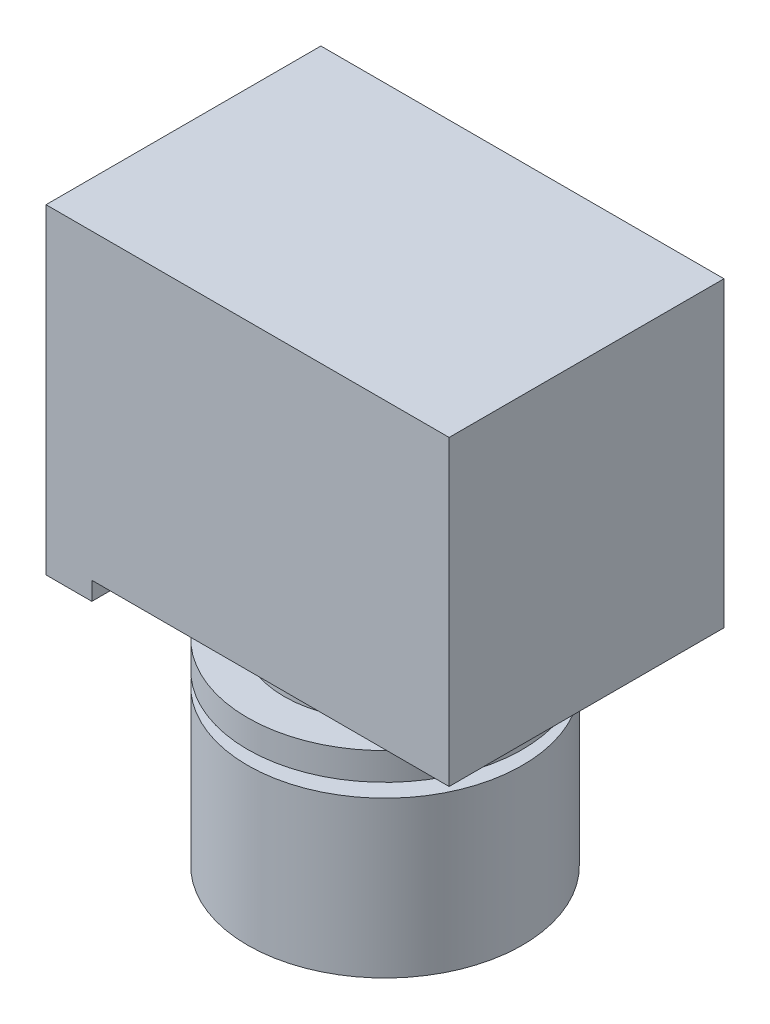
SolidWorks part; units mm, degrees
ref_plane "前基準面" through (0, 0, 0) normal (0, 0, 1) x (1, 0, 0)
ref_plane "上基準面" through (0, 0, 0) normal (0, 1, 0) x (1, 0, 0)
ref_plane "右基準面" through (0, 0, 0) normal (1, 0, 0) x (0, 0, -1)
sketch "草圖1" plane through (0, 0, 0) normal (0, 1, 0) x (1, 0, 0)
  circle A0 centre (0, 0) radius 15
  dimension "D1" = 30
extrude "伸長1" add sketch "草圖1" along normal blind 17
sketch "草圖2" plane through (0, 17, 0) normal (0, 1, 0) x (1, 0, 0)
  circle A0 centre (0, 0) radius 11
  dimension "D1" = 22
extrude "伸長2" add sketch "草圖2" along normal blind 1.5
sketch "草圖3" plane through (0, 18.5, 0) normal (0, 1, 0) x (1, 0, 0)
  circle A0 centre (0, 0) radius 15
  dimension "D1" = 30
extrude "伸長3" add sketch "草圖3" along normal blind 3
sketch "草圖4" plane through (0, 21.5, 0) normal (0, 1, 0) x (1, 0, 0)
  circle A0 centre (0, 0) radius 11
  dimension "D1" = 22
extrude "伸長4" add sketch "草圖4" along normal blind 4.5
cosmetic thread "裝飾螺紋線1" parameters "D2"=20.5
sketch "草圖6" plane through (0, 26, 0) normal (0, 1, 0) x (1, 0, 0)
  line L0 (0, 0) -> (22, 0) construction
  line L1 (-22, 15) -> (22, 15)
  line L2 (-22, 15) -> (-22, -15)
  line L3 (-22, -15) -> (22, -15)
  line L4 (22, 15) -> (22, -15)
  line L5 (0, 0) -> (0, -15) construction
  dimension "D1" = 30
  dimension "D2" = 44
extrude "伸長6" add sketch "草圖6" along normal blind 33
sketch "草圖7" plane through (0, 26, 0) normal (0, -1, 0) x (1, 0, 0)
  line L0 (22, -15) -> (-22, -15) construction
  line L1 (-22, 15) -> (-17, 15)
  line L2 (-22, 15) -> (-22, -15)
  line L3 (-22, -15) -> (-17, -15)
  line L4 (-17, 15) -> (-17, -15)
  dimension "D1" = 5
extrude "伸長7" add sketch "草圖7" along normal blind 2
sketch "草圖9" plane through (0, 0, 0) normal (0, -1, 0) x (1, 0, 0)
  circle A0 centre (0, 0) radius 13
  circle A1 centre (0, 0) radius 12
  dimension "D1" = 24
  dimension "D2" = 26
extrude "除料-伸長2" cut sketch "草圖9" against normal blind 2
